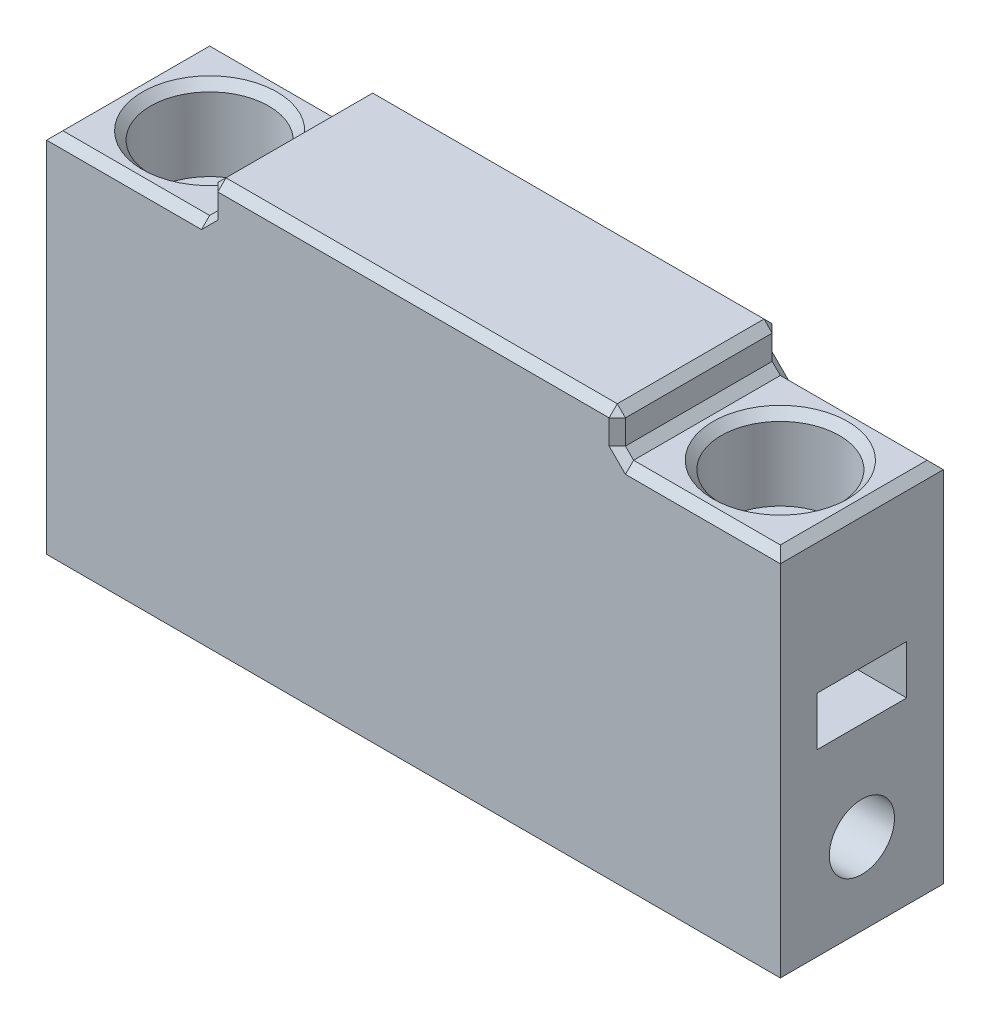
SolidWorks part; units mm, degrees
ref_plane "Front Plane" through (0, 0, 0) normal (0, 0, 1) x (1, 0, 0)
ref_plane "Top Plane" through (0, 0, 0) normal (0, 1, 0) x (1, 0, 0)
ref_plane "Right Plane" through (0, 0, 0) normal (1, 0, 0) x (0, 0, -1)
sketch "Sketch1" plane through (0, 0, 0) normal (0, 0, 1) x (1, 0, 0)
  line L1 (25, -25) -> (-25, -25)
  line L2 (25, -25) -> (25, 25) construction
  line L4 (-25, -25) -> (-25, 25) construction
  line L5 (25, -25) -> (-25, 25) construction
  line L6 (25, 25) -> (-25, -25) construction
  line L9 (0, -1000) -> (0, 49000) construction
  line L10 (-25, -25) -> (-45, -25)
  line L12 (-25, 20) -> (-45, 20)
  line L13 (-45, -25) -> (-45, 20)
  line L14 (25, 20) -> (45, 20)
  line L15 (45, -25) -> (45, 20)
  line L16 (25, -25) -> (45, -25)
  line L17 (-25, 20) -> (-25, 25)
  line L18 (25, 20) -> (25, 25)
  line L19 (-25, 25) -> (25, 25)
  point P0 (0, 0)
  dimension "D3" = 45
  dimension "D2" = 50
  dimension "D5" = 20
extrude "Body" add sketch "Sketch1" along normal mid plane 20
sketch "Sketch14" plane through (0, 0, -10) normal (0, 0, -1) x (-1, 0, 0)
  line L0 (-25, 25) -> (25, -25) construction
  line L1 (45, -25) -> (-45, -25) construction
  circle A0 centre (0, 0) radius 7.5
  dimension "D1" = 15
extrude "Bearing_Support" add sketch "Sketch14" along normal blind 7
sketch "Sketch15" plane through (0, 0, -17) normal (0, 0, -1) x (-1, 0, 0)
  circle A0 centre (0, 0) radius 4.7
  circle A1 centre (0, 0) radius 7.5
  circle A2 centre (0, 0) radius 7.5
  dimension "D2" = 9.4
  dimension "D1" = 0
extrude "Bearing_Place" add sketch "Sketch15" along normal blind 4
sketch "Sketch16" plane through (0, 0, -17) normal (0, 0, -1) x (-1, 0, 0)
  circle A0 centre (0, 0) radius 2
  dimension "D1" = 4
extrude "Motor_Shaft_Hole" cut sketch "Sketch16" against normal blind 3
fillet "Fillet1" radius 6 1 edges at (-7.5, 0, -10)
sketch "Sketch17" plane through (0, 20, 0) normal (0, 1, 0) x (1, 0, 0)
  line L0 (-45, 10) -> (-25, -10) construction
  circle A0 centre (-35, 0) radius 7.25
  dimension "D1" = 14.5
extrude "Spring_Hole" cut sketch "Sketch17" against normal blind 10
sketch "Sketch18" plane through (-45, 0, 0) normal (-1, 0, 0) x (0, 0, 1)
  line L1 (5.5, -3) -> (-5.5, -3)
  line L2 (5.5, -3) -> (5.5, 3)
  line L3 (5.5, 3) -> (-5.5, 3)
  line L4 (-5.5, -3) -> (-5.5, 3)
  line L5 (5.5, -3) -> (-5.5, 3) construction
  line L6 (5.5, 3) -> (-5.5, -3) construction
  line L7 (10, 20) -> (-10, 20) construction
  point P0 (0, 0)
  dimension "D1" = 11
  dimension "D2" = 6
  dimension "D3" = 20
extrude "Nut_Hole" cut sketch "Sketch18" against normal blind 20
sketch "Sketch19" plane through (0, 10, 0) normal (0, 1, 0) x (1, 0, 0)
  circle A0 centre (-35, 0) radius 3.25
  dimension "D1" = 6.5
extrude "Shaft_Hole" cut sketch "Sketch19" against normal up to surface (13 mm away) up to face at (-35, -3, 0)
sketch "Sketch20" plane through (45, 0, 0) normal (1, 0, 0) x (0, 0, -1)
  line L1 (-10, 20) -> (10, 20) construction
  circle A0 centre (0, -15) radius 4
  dimension "D1" = 8
  dimension "D2" = 35
extrude "Brake_Screw_Hole" cut sketch "Sketch20" against normal blind 20
sketch "Sketch21" plane through (0, -25, 0) normal (0, -1, 0) x (1, 0, 0)
  line L1 (31, -5.5) -> (25, -5.5)
  line L2 (31, -5.5) -> (31, 5.5)
  line L3 (31, 5.5) -> (25, 5.5)
  line L4 (25, -5.5) -> (25, 5.5)
  line L5 (31, -5.5) -> (25, 5.5) construction
  line L6 (31, 5.5) -> (25, -5.5) construction
  line L7 (45, 10) -> (45, -10) construction
  point P0 (28, 0)
  dimension "D1" = 11
  dimension "D2" = 6
  dimension "D3" = 14
extrude "Brake_Nut_Hole" cut sketch "Sketch21" against normal blind 20
mirror "Mirror1" about plane through (0, 0, 0) normal (1, 0, 0) of "Brake_Screw_Hole", "Brake_Nut_Hole", "Shaft_Hole", "Nut_Hole", "Spring_Hole"
chamfer "Chamfer1" distance 1 angle 45 18 edges at (25, 25, 0) (0, 25, 10) (-25, 25, 0) (0, 25, -10) (-25, 22.5, 10) (-25, 22.5, -10) (-25, 20, 0) (-35, 20, 10) (-45, 20, 0) (-35, 20, -10) (-42.25, 20, 0) (25, 22.5, 10) (25, 22.5, -10) (45, 20, 0) (35, 20, 10) (25, 20, 0) (35, 20, -10) (42.25, 20, 0)
